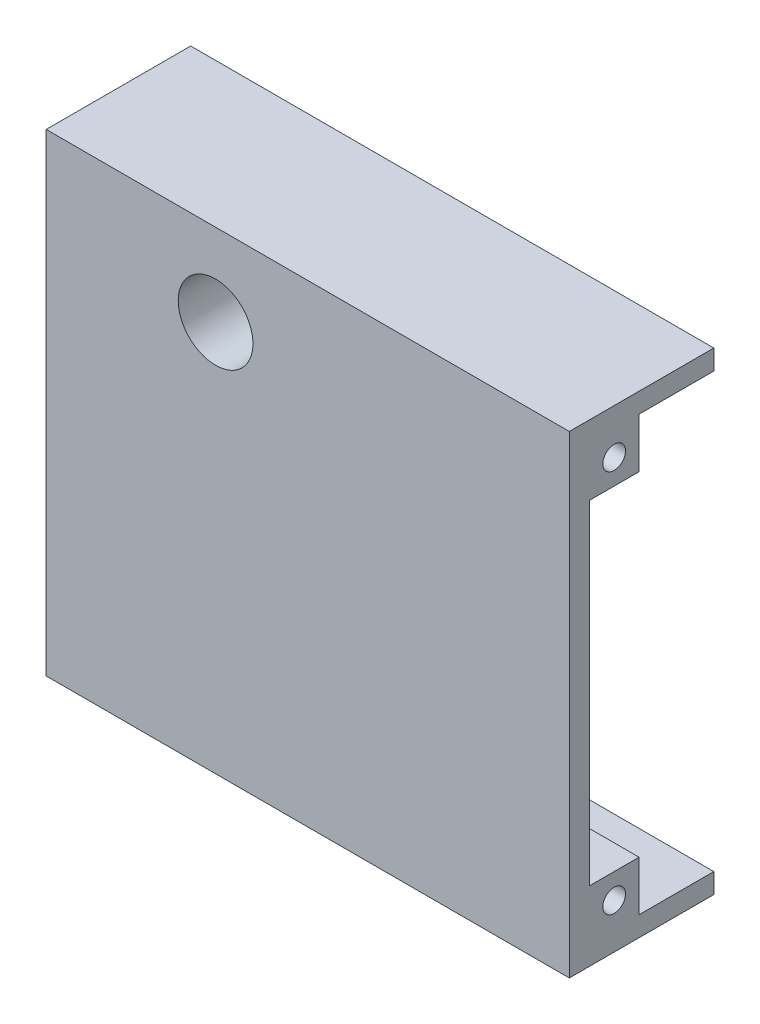
SolidWorks part; units mm, degrees
ref_plane "정면" through (0, 0, 0) normal (0, 0, 1) x (1, 0, 0)
ref_plane "윗면" through (0, 0, 0) normal (0, 1, 0) x (1, 0, 0)
ref_plane "우측면" through (0, 0, 0) normal (1, 0, 0) x (0, 0, -1)
sketch "스케치1" plane through (0, 0, 0) normal (0, 0, 1) x (1, 0, 0)
  line L1 (-105, 95) -> (105, 95)
  line L2 (-105, 95) -> (-105, -95)
  line L3 (-105, -95) -> (105, -95)
  line L4 (105, 95) -> (105, -95)
  line L5 (-105, 95) -> (105, -95) construction
  line L6 (-105, -95) -> (105, 95) construction
  point P0 (0, 0)
  dimension "D1" = 210
  dimension "D2" = 190
extrude "보스-돌출1" add sketch "스케치1" along normal blind 8
sketch "스케치2" plane through (0, 0, 0) normal (0, 0, -1) x (-1, 0, 0)
  line L0 (-105, 95) -> (105, 95)
  line L1 (105, 95) -> (105, -95)
  line L2 (105, -95) -> (-105, -95)
  line L3 (-105, -95) -> (-105, -87)
  line L4 (-105, -95) -> (-105, 95) construction
  line L5 (-105, -87) -> (97, -87)
  line L6 (97, -87) -> (97, 87)
  line L7 (97, 87) -> (-105, 87)
  line L8 (-105, 87) -> (-105, 95)
  dimension "D1" = 8
  dimension "D2" = 8
  dimension "D3" = 8
extrude "보스-돌출2" add sketch "스케치2" along normal blind 50
sketch "스케치3" plane through (105, 0, 0) normal (1, 0, 0) x (0, 0, -1)
  line L1 (0, 87) -> (20, 87)
  line L2 (0, 87) -> (0, 67)
  line L3 (0, 67) -> (20, 67)
  line L4 (20, 87) -> (20, 67)
  dimension "D1" = 20
  dimension "D2" = 20
extrude "보스-돌출3" add sketch "스케치3" against normal blind 20
sketch "스케치8" plane through (105, 0, 0) normal (1, 0, 0) x (0, 0, -1)
  line L0 (0, 67) -> (20, 67) construction
  line L1 (20, 67) -> (20, 87) construction
  circle A0 centre (10, 77) radius 4.55
  dimension "D1" = 9.1
  dimension "D3" = 10
  dimension "D2" = 10
extrude "컷-돌출1" cut sketch "스케치8" against normal blind 25
ref_plane "평면1" through (0, 0, 0) normal (0, -1, 0) x (-1, 0, 0)
mirror "대칭 복사1" about plane through (0, 0, 0) normal (0, -1, 0) of "컷-돌출1", "보스-돌출3"
sketch "스케치9" plane through (0, 0, 0) normal (0, 0, -1) x (-1, 0, 0)
  line L0 (-85, 87) -> (97, 87) construction
  line L1 (97, 37) -> (-23, 37)
  line L2 (97, 37) -> (97, 87)
  line L3 (97, 87) -> (-23, 87)
  line L4 (-23, 37) -> (-23, 87)
  line L5 (97, 87) -> (97, -87) construction
  point P5 (-32.2805, 87)
  point P8 (97, 37)
  dimension "D1" = 120
  dimension "D2" = 50
extrude "보스-돌출4" add sketch "스케치9" along normal blind 25
sketch "스케치10" plane through (0, 0, -25) normal (0, 0, -1) x (-1, 0, 0)
  line L0 (97, 87) -> (-23, 87) construction
  line L6 (-23, 87) -> (-23, 37) construction
  circle A0 centre (37, 62) radius 15
  dimension "D3" = 30
  dimension "D2" = 25
  dimension "D1" = 60
extrude "컷-돌출2" cut sketch "스케치10" against normal through all
